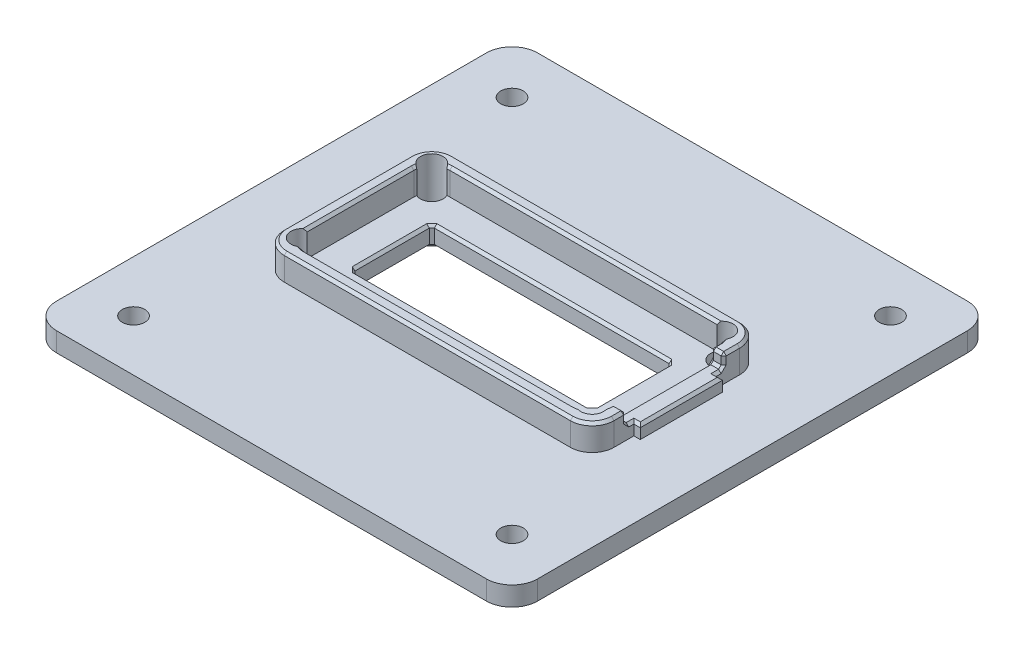
SolidWorks part; units mm, degrees
ref_plane "前视基准面" through (0, 0, 0) normal (0, 0, 1) x (1, 0, 0)
ref_plane "上视基准面" through (0, 0, 0) normal (0, 1, 0) x (1, 0, 0)
ref_plane "右视基准面" through (0, 0, 0) normal (1, 0, 0) x (0, 0, -1)
sketch "草图1" plane through (0, 0, 0) normal (0, 1, 0) x (1, 0, 0)
  line L1 (-37.5, 37.5) -> (37.5, 37.5)
  line L2 (-37.5, 37.5) -> (-37.5, -37.5)
  line L3 (-37.5, -37.5) -> (37.5, -37.5)
  line L4 (37.5, 37.5) -> (37.5, -37.5)
  line L5 (-37.5, 37.5) -> (37.5, -37.5) construction
  line L6 (-37.5, -37.5) -> (37.5, 37.5) construction
  line L7 (-18.7, 6.2) -> (18.7, 6.2)
  line L8 (-18.7, 6.2) -> (-18.7, -6.2)
  line L9 (-18.7, -6.2) -> (18.7, -6.2)
  line L10 (18.7, 6.2) -> (18.7, -6.2)
  line L11 (-18.7, 6.2) -> (18.7, -6.2) construction
  line L12 (-18.7, -6.2) -> (18.7, 6.2) construction
  circle A0 centre (-29.5, 29.5) radius 1.75
  circle A1 centre (29.5, 29.5) radius 1.75
  circle A2 centre (29.5, -29.5) radius 1.75
  circle A3 centre (-29.5, -29.5) radius 1.75
  point P0 (0, 0)
  point P14 (0, 0)
  dimension "D3" = 3.5
  dimension "D5" = 8
  dimension "D6" = 8
  dimension "D7" = 8
  dimension "D1" = 75
  dimension "D2" = 75
  dimension "D4" = 8
  dimension "D8" = 37.4
  dimension "D9" = 12.4
extrude "凸台-拉伸1" add sketch "草图1" along normal blind 3
sketch "草图2" plane through (0, 3, 0) normal (0, 1, 0) x (1, 0, 0)
  line L1 (-23.7, 11.2) -> (23.7, 11.2)
  line L2 (-23.7, 11.2) -> (-23.7, -11.2)
  line L3 (-23.7, -11.2) -> (23.7, -11.2)
  line L4 (23.7, 11.2) -> (23.7, -11.2)
  line L5 (-23.7, 11.2) -> (23.7, -11.2) construction
  line L6 (-23.7, -11.2) -> (23.7, 11.2) construction
  line L7 (-25.7, 13.2) -> (25.7, 13.2)
  line L8 (-25.7, 13.2) -> (-25.7, -13.2)
  line L9 (-25.7, -13.2) -> (25.7, -13.2)
  line L10 (25.7, 13.2) -> (25.7, -13.2)
  line L11 (-25.7, 13.2) -> (25.7, -13.2) construction
  line L12 (-25.7, -13.2) -> (25.7, 13.2) construction
  point P0 (0, 0)
  point P6 (0, 0)
  dimension "D1" = 47.4
  dimension "D2" = 22.4
  dimension "D3" = 2
  dimension "D4" = 2
extrude "凸台-拉伸2" add sketch "草图2" along normal blind 4
sketch "草图3" plane through (0, 7, 0) normal (0, 1, 0) x (1, 0, 0)
  line L0 (23.7, -11.2) -> (23.7, 11.2) construction
  line L1 (23.7, 7.3) -> (25.7, 7.3)
  line L2 (23.7, 7.3) -> (23.7, -7.9)
  line L3 (23.7, -7.9) -> (25.7, -7.9)
  line L4 (25.7, 7.3) -> (25.7, -7.9)
  line L5 (25.7, -13.2) -> (25.7, 13.2) construction
  line L6 (25.7, 13.2) -> (-25.7, 13.2) construction
  dimension "D1" = 15.2
  dimension "D2" = 5.9
extrude "切除-拉伸1" cut sketch "草图3" against normal blind 2
sketch "草图4" plane through (0, 3, 0) normal (0, 1, 0) x (1, 0, 0)
  line L0 (25.7, -7.9) -> (25.7, 7.3) construction
  line L1 (25.7, 6.1) -> (26.7, 6.1)
  line L2 (25.7, 6.1) -> (25.7, -6.7)
  line L3 (25.7, -6.7) -> (26.7, -6.7)
  line L4 (26.7, 6.1) -> (26.7, -6.7)
  line L5 (25.7, 7.3) -> (23.7, 7.3) construction
  dimension "D1" = 1
  dimension "D2" = 12.8
  dimension "D3" = 1.2
extrude "凸台-拉伸3" add sketch "草图4" along normal blind 2
sketch "草图5" plane through (0, 3, 0) normal (0, 1, 0) x (1, 0, 0)
  line L0 (25.7, 6.1) -> (25.7, 13.2) construction
  line L1 (-25.7, -13.2) -> (25.7, -13.2) construction
  circle A0 centre (-22.91, 10.4) radius 1.75
  circle A1 centre (22.3, 10.4) radius 1.75
  circle A2 centre (22.3, -9.8) radius 1.75
  circle A3 centre (-22.91, -9.8) radius 1.75
  point P8 (0, 0)
  point P9 (0, 0)
  dimension "D1" = 3.5
  dimension "D2" = 3.4
  dimension "D3" = 45.21
  dimension "D4" = 20.2
  dimension "D5" = 3.4
fillet "圆角1" radius 2.8 4 edges at (23.7, 5, 11.2) (-23.7, 5, 11.2) (23.7, 5, -11.2) (-23.7, 5, -11.2)
fillet "圆角2" radius 3.4 4 edges at (25.7, 5, -13.2) (25.7, 5, 13.2) (-25.7, 5, 13.2) (-25.7, 5, -13.2)
chamfer "倒角1" distance 0.4 angle 45 44 edges at (18.7, 1.5, -6.2) (18.7, 3, 0) (18.7, 1.5, 6.2) (18.7, 0, 0) (0, 3, 6.2) (0, 0, 6.2) (0, 3, -6.2) (0, 0, -6.2) (-18.7, 1.5, 6.2) (-18.7, 3, 0) (-18.7, 1.5, -6.2) (-18.7, 0, 0) (24.7, 7, -7.3) (23.7, 7, -7.85) (22.8799, 7, -10.3799) (0, 7, -11.2) (-22.8799, 7, -10.3799) (-23.7, 7, 0) (-22.8799, 7, 10.3799) (0, 7, 11.2) (22.8799, 7, 10.3799) (23.7, 7, 8.15) (24.7, 7, 7.9) (25.7, 7, 8.85) (24.7042, 7, 12.2042) (0, 7, 13.2) (-24.7042, 7, 12.2042) (-25.7, 7, 0) (-24.7042, 7, -12.2042) (0, 7, -13.2) (24.7042, 7, -12.2042) (25.7, 7, -8.55) (25.7, 6, -7.3) (23.7, 6, -7.3) (25.7, 6, 7.9) (23.7, 6, 7.9) (24.7, 5, -7.3) (25.7, 5, -6.7) (26.2, 5, -6.1) (26.7, 5, 0.3) (26.2, 5, 6.7) (25.7, 5, 7.3) (24.7, 5, 7.9) (23.7, 5, 0.3)
extrude "切除-拉伸2" cut sketch "草图5" against normal up to next and the other way through all
fillet "圆角3" radius 4 4 edges at (-37.5, 1.5, 37.5) (37.5, 1.5, 37.5) (37.5, 1.5, -37.5) (-37.5, 1.5, -37.5)
